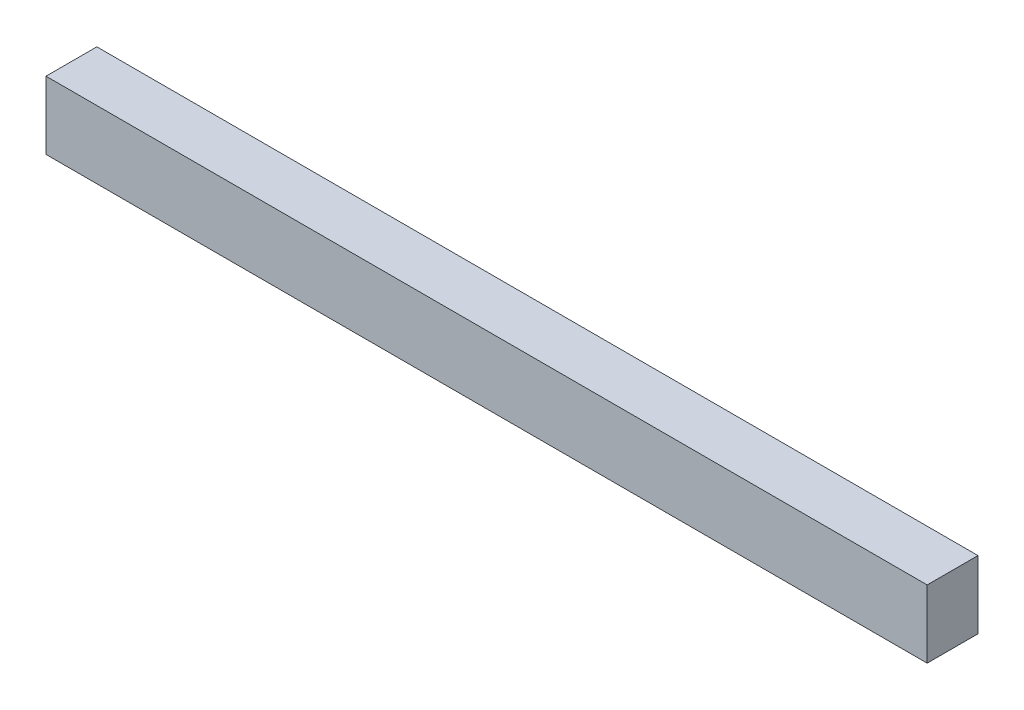
SolidWorks part; units mm, degrees
ref_plane "Plan de face" through (0, 0, 0) normal (0, 0, 1) x (1, 0, 0)
ref_plane "Plan de dessus" through (0, 0, 0) normal (0, 1, 0) x (1, 0, 0)
ref_plane "Plan de droite" through (0, 0, 0) normal (1, 0, 0) x (0, 0, -1)
sketch "Esquisse1" plane through (0, 0, 0) normal (0, 0, 1) x (1, 0, 0)
  line L1 (0, 0) -> (520, 0)
  line L2 (0, 0) -> (0, 40)
  line L3 (0, 40) -> (520, 40)
  line L4 (520, 0) -> (520, 40)
  dimension "D1" = 40
  dimension "D2" = 520
extrude "Boss.-Extru.1" add sketch "Esquisse1" along normal blind 30
